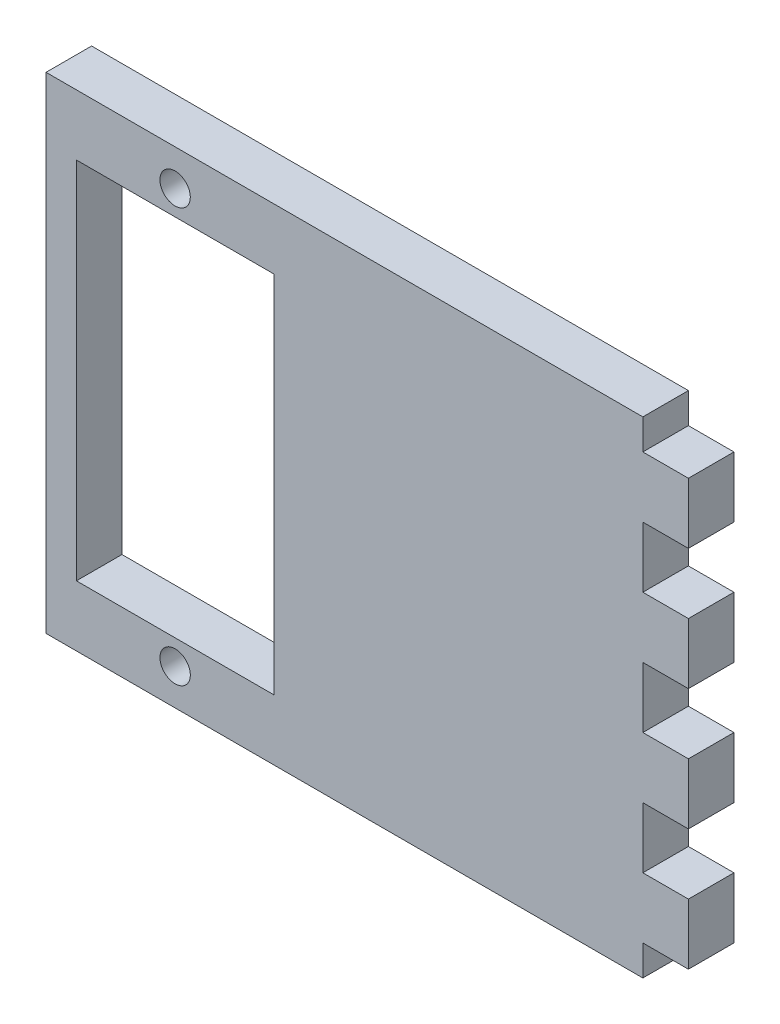
SolidWorks part; units mm, degrees
ref_plane "Front Plane" through (0, 0, 0) normal (0, 0, 1) x (1, 0, 0)
ref_plane "Top Plane" through (0, 0, 0) normal (0, 1, 0) x (1, 0, 0)
ref_plane "Right Plane" through (0, 0, 0) normal (1, 0, 0) x (0, 0, -1)
sketch "Sketch1" plane through (0, 0, 0) normal (0, 0, 1) x (1, 0, 0)
  line L0 (30.8, 14) -> (33.8, 14)
  line L1 (-8.5, -16) -> (30.8, -16)
  line L2 (-8.5, -16) -> (-8.5, 16)
  line L3 (-8.5, 16) -> (30.8, 16)
  line L4 (30.8, -16) -> (30.8, -14)
  line L7 (33.8, 14) -> (33.8, 10)
  line L8 (33.8, 10) -> (30.8, 10)
  line L9 (30.8, 6) -> (33.8, 6)
  line L10 (33.8, 6) -> (33.8, 2)
  line L11 (33.8, 2) -> (30.8, 2)
  line L12 (30.8, -14) -> (33.8, -14)
  line L13 (33.8, -14) -> (33.8, -10)
  line L14 (33.8, -10) -> (30.8, -10)
  line L15 (30.8, -6) -> (33.8, -6)
  line L16 (33.8, -6) -> (33.8, -2)
  line L17 (33.8, -2) -> (30.8, -2)
  line L18 (30.8, 14) -> (30.8, 16)
  line L19 (30.8, 6) -> (30.8, 10)
  line L20 (30.8, -2) -> (30.8, 2)
  line L21 (30.8, -10) -> (30.8, -6)
  line L22 (0, 0) -> (6.5, 0) construction
  line L23 (6.5, -12) -> (-6.5, -12)
  line L24 (6.5, -12) -> (6.5, 12)
  line L25 (6.5, 12) -> (-6.5, 12)
  line L26 (-6.5, -12) -> (-6.5, 12)
  line L27 (6.5, -12) -> (-6.5, 12) construction
  line L28 (6.5, 12) -> (-6.5, -12) construction
  circle A0 centre (0, 13.625) radius 1
  circle A1 centre (0, -13.625) radius 1
  point P0 (0, 0)
  point P20 (0, 0)
  point P33 (30.8, 0)
  point P34 (-8.5, 0)
  dimension "D5" = 2
  dimension "D1" = 32
  dimension "D2" = 4
  dimension "D3" = 24
  dimension "D4" = 13.625
  dimension "D6" = 13
  dimension "D7" = 39.3
  dimension "D8" = 3
  dimension "D9" = 4
  dimension "D10" = 2
extrude "Boss-Extrude1" add sketch "Sketch1" along normal blind 3
